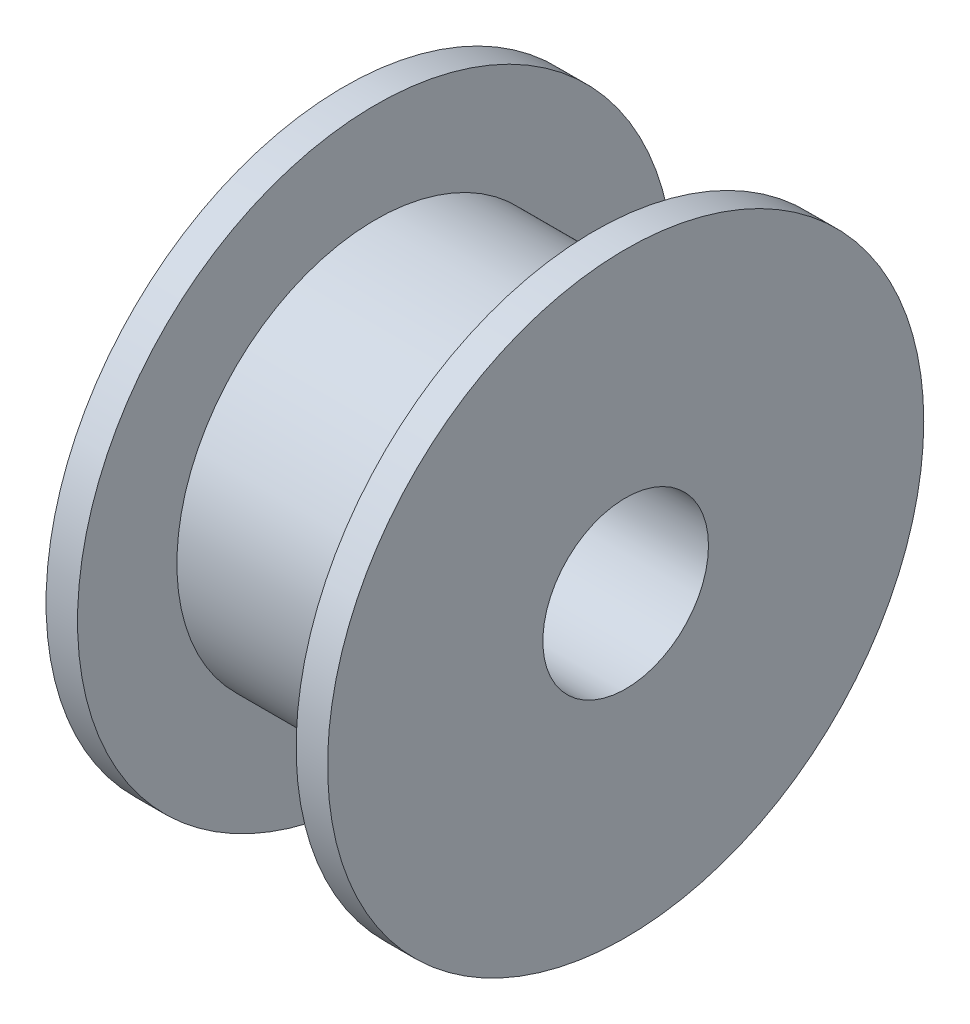
SolidWorks part; units mm, degrees
material "6061-T6 (SS)"
ref_plane "Front Plane" through (0, 0, 0) normal (0, 0, 1) x (1, 0, 0)
ref_plane "Top Plane" through (0, 0, 0) normal (0, 1, 0) x (1, 0, 0)
ref_plane "Right Plane" through (0, 0, 0) normal (1, 0, 0) x (0, 0, -1)
sketch "Sketch1" plane through (0, 0, 0) normal (0, 0, 1) x (1, 0, 0)
  line L0 (0, 2.5) -> (0, 9)
  line L1 (0, 9) -> (0.95, 9)
  line L2 (0.95, 9) -> (0.95, 6)
  line L3 (0.95, 6) -> (7.55, 6)
  line L4 (7.55, 6) -> (7.55, 9)
  line L5 (7.55, 9) -> (8.5, 9)
  line L6 (8.5, 9) -> (8.5, 2.5)
  line L7 (8.5, 2.5) -> (0, 2.5)
  line L8 (0, 0) -> (-7.6744, 0) construction
  point P1 (0, 0)
  dimension "D1" = 5
  dimension "D2" = 18
  dimension "D3" = 12
  dimension "D5" = 8.5
  dimension "D6" = 0.95
revolve "Revolve1" add sketch "Sketch1" angle 360 about L8
